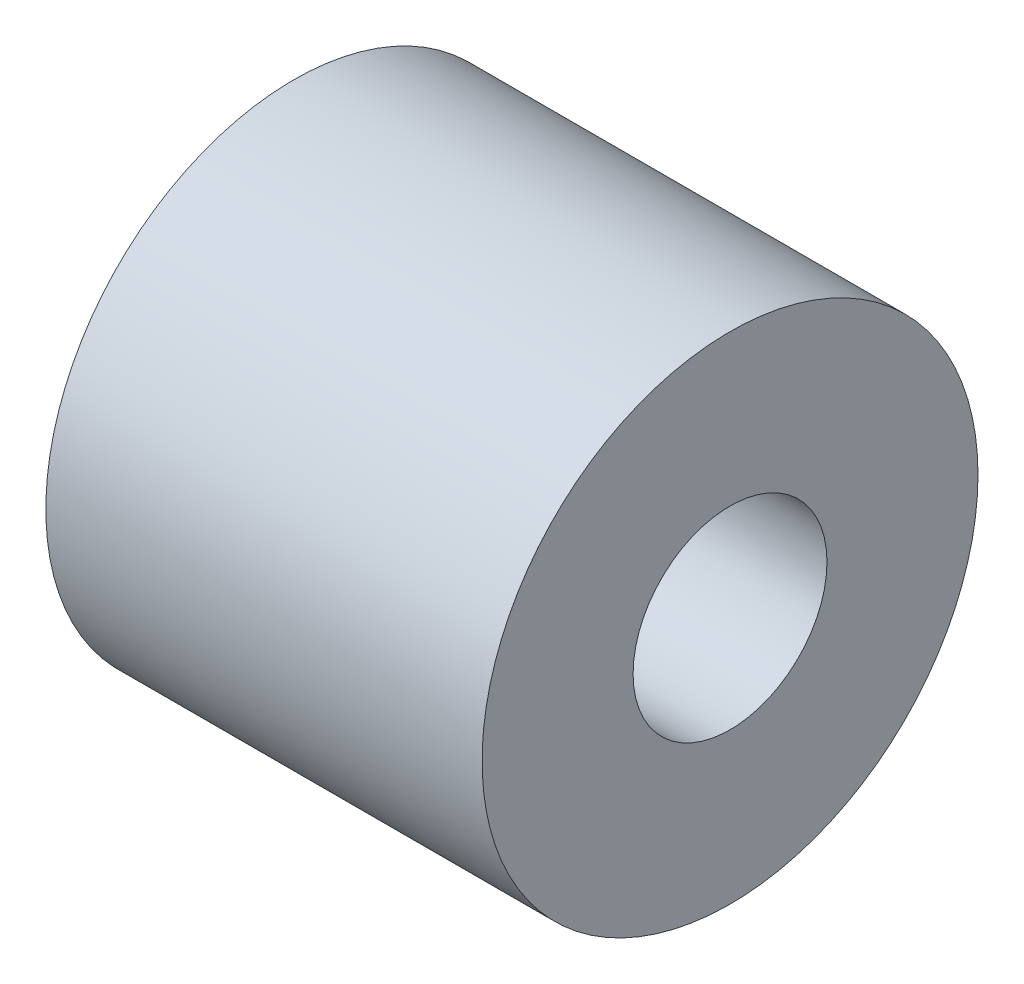
SolidWorks part; units mm, degrees
ref_plane "Front Plane" through (0, 0, 0) normal (0, 0, 1) x (1, 0, 0)
ref_plane "Top Plane" through (0, 0, 0) normal (0, 1, 0) x (1, 0, 0)
ref_plane "Right Plane" through (0, 0, 0) normal (1, 0, 0) x (0, 0, -1)
sketch "Sketch1" plane through (0, 0, 0) normal (1, 0, 0) x (0, 0, -1)
  circle A0 centre (0, 0) radius 6.65
  circle A1 centre (0, 0) radius 2.6
  dimension "D1" = 13.3
  dimension "D2" = 5.2
extrude "Boss-Extrude1" add sketch "Sketch1" along normal blind 11.7
